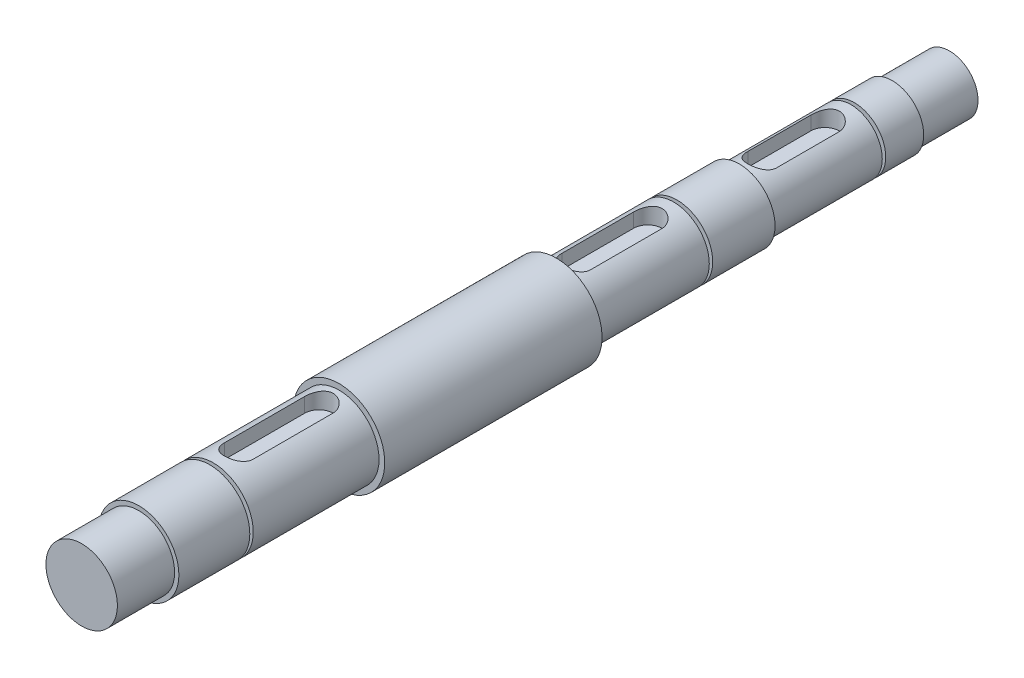
SolidWorks part; units mm, degrees
ref_plane "Front Plane" through (0, 0, 0) normal (0, 0, 1) x (1, 0, 0)
ref_plane "Top Plane" through (0, 0, 0) normal (0, 1, 0) x (1, 0, 0)
ref_plane "Right Plane" through (0, 0, 0) normal (1, 0, 0) x (0, 0, -1)
sketch "Sketch2" plane through (0, 0, 0) normal (0, 0, 1) x (1, 0, 0)
  circle A0 centre (0, 0) radius 12.5
  dimension "D1" = 25
extrude "Boss-Extrude1" add sketch "Sketch2" along normal blind 20
sketch "Sketch3" plane through (0, 0, 0) normal (0, 0, -1) x (-1, 0, 0)
  circle A0 centre (0, 0) radius 14
  dimension "D1" = 28
extrude "Boss-Extrude2" add sketch "Sketch3" along normal blind 70
sketch "Sketch4" plane through (0, 0, -70) normal (0, 0, -1) x (-1, 0, 0)
  circle A0 centre (0, 0) radius 16
  dimension "D1" = 32
extrude "Boss-Extrude3" add sketch "Sketch4" along normal blind 76
sketch "Sketch5" plane through (0, 0, -146) normal (0, 0, -1) x (-1, 0, 0)
  circle A0 centre (0, 0) radius 12.5
  dimension "D1" = 25
extrude "Boss-Extrude4" add sketch "Sketch5" along normal blind 64
sketch "Sketch6" plane through (0, 0, -210) normal (0, 0, -1) x (-1, 0, 0)
  circle A0 centre (0, 0) radius 11
  dimension "D1" = 22
extrude "Boss-Extrude5" add sketch "Sketch6" along normal blind 53.5
sketch "Sketch7" plane through (0, 0, -263.5) normal (0, 0, -1) x (-1, 0, 0)
  circle A0 centre (0, 0) radius 10
  dimension "D1" = 20
extrude "Boss-Extrude6" add sketch "Sketch7" along normal blind 20
ref_plane "Plane1" through (0, 14, 0) normal (0, 1, 0) x (1, 0, 0)
sketch "Sketch8" plane through (0, 14, 0) normal (0, 1, 0) x (1, 0, 0)
  line L0 (0, 0) -> (0, 71.4854) construction
  line L1 (0, 63) -> (0, 35) construction
  line L2 (5, 63) -> (5, 35)
  line L3 (-5, 63) -> (-5, 35)
  arc A0 (5, 63) -> (-5, 63) centre (0, 63) ccw
  arc A1 (-5, 35) -> (5, 35) centre (0, 35) ccw
  point P5 (0, 49)
  dimension "D1" = 35
  dimension "D2" = 28
  dimension "D3" = 10
extrude "Cut-Extrude1" cut sketch "Sketch8" against normal blind 6
ref_plane "Plane2" through (0, 12.5, 0) normal (0, 1, 0) x (1, 0, 0)
sketch "Sketch9" plane through (0, 12.5, 0) normal (0, 1, 0) x (1, 0, 0)
  line L0 (0, 153) -> (0, 178) construction
  line L1 (-5, 153) -> (-5, 178)
  line L2 (5, 153) -> (5, 178)
  line L3 (12.5, 146) -> (-12.5, 146) construction
  arc A0 (-5, 153) -> (5, 153) centre (0, 153) ccw
  arc A1 (5, 178) -> (-5, 178) centre (0, 178) ccw
  point P3 (0, 165.5)
  dimension "D1" = 7
  dimension "D2" = 10
  dimension "D3" = 25
extrude "Cut-Extrude2" cut sketch "Sketch9" against normal blind 6
ref_plane "Plane3" through (0, 11, 0) normal (0, 1, 0) x (1, 0, 0)
sketch "Sketch11" plane through (0, 11, 0) normal (0, 1, 0) x (1, 0, 0)
  line L0 (0, 218) -> (0, 240) construction
  line L1 (-5, 218) -> (-5, 240)
  line L2 (5, 218) -> (5, 240)
  line L3 (11, 210) -> (-11, 210) construction
  arc A0 (-5, 218) -> (5, 218) centre (0, 218) ccw
  arc A1 (5, 240) -> (-5, 240) centre (0, 240) ccw
  point P3 (0, 229)
  dimension "D1" = 22
  dimension "D2" = 10
  dimension "D3" = 8
extrude "Cut-Extrude3" cut sketch "Sketch11" against normal blind 6
sketch "Sketch12" plane through (0, 0, 0) normal (1, 0, 0) x (0, 0, -1)
  line L6 (26, 14) -> (26, 12.2)
  line L7 (30.0001, 14) -> (0, 14) construction
  line L8 (26, 12.2) -> (24.8, 12.2)
  line L9 (24.8, 12.2) -> (24.8, 14)
  line L10 (24.8, 14) -> (26, 14)
  line L11 (187, 12.5) -> (187, 10.7)
  line L12 (210, 12.5) -> (183, 12.5) construction
  line L13 (187, 10.7) -> (188.2, 10.7)
  line L14 (188.2, 10.7) -> (188.2, 12.5)
  line L15 (249, 11) -> (249, 9.2)
  line L16 (263.5, 11) -> (245, 11) construction
  line L17 (249, 9.2) -> (250.2, 9.2)
  line L18 (250.2, 9.2) -> (250.2, 11)
  line L19 (250.2, 11) -> (249, 11)
  line L20 (-20.6792, 0) -> (282.6564, 0) construction
  line L21 (187, 12.5) -> (188.2, 12.5)
  dimension "D4" = 4
  dimension "D5" = 1.2
  dimension "D6" = 1.8
  dimension "D7" = 4
  dimension "D8" = 1.8
  dimension "D9" = 1.2
  dimension "D10" = 4
  dimension "D11" = 1.8
  dimension "D12" = 1.2
revolve "Cut-Revolve1" cut sketch "Sketch12" angle 360 about L20
sketch "Sketch13" plane through (0, 0, 0) normal (1, 0, 0) x (0, 0, -1)
  line L0 (282, 10) -> (282, 8.2)
  line L1 (283.5, 10) -> (263.5, 10) construction
  line L2 (283.5, -10) -> (283.5, 10) construction
  line L3 (282, 8.2) -> (280.8, 8.2)
  line L4 (280.8, 8.2) -> (280.8, 10)
  line L5 (280.8, 10) -> (282, 10)
  line L6 (282, 0) -> (237.0555, 0) construction
  dimension "D1" = 1.5
  dimension "D2" = 1.8
  dimension "D3" = 1.2
